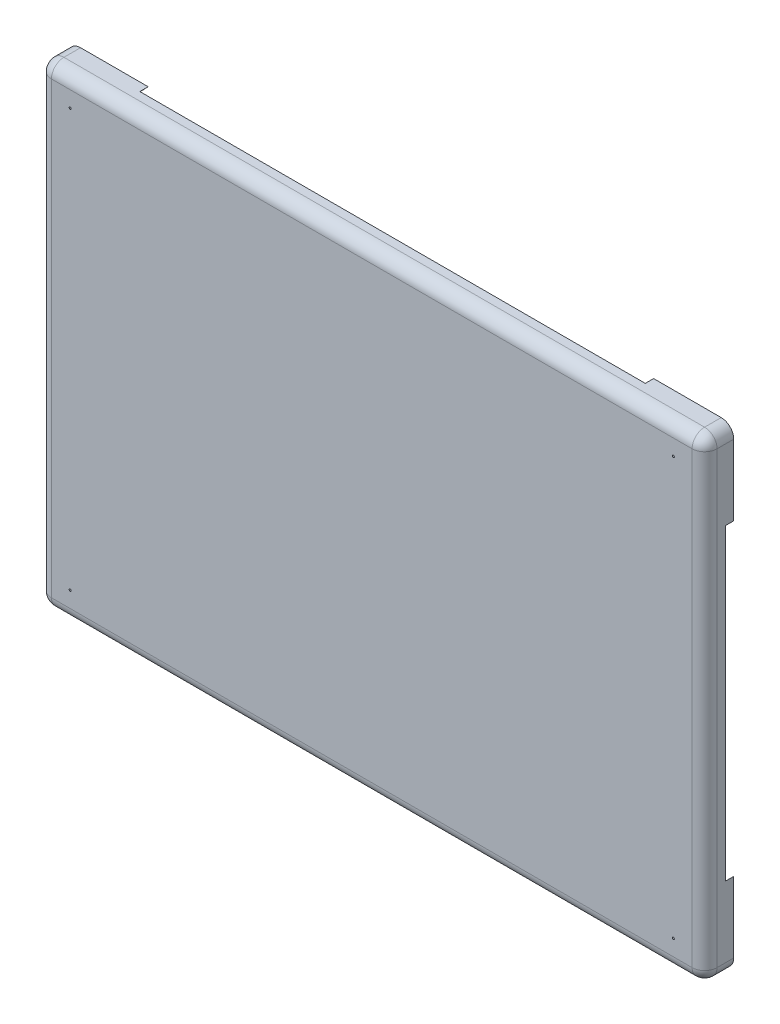
SolidWorks part; units mm, degrees
ref_plane "Front Plane" through (0, 0, 0) normal (0, 0, 1) x (1, 0, 0)
ref_plane "Top Plane" through (0, 0, 0) normal (0, 1, 0) x (1, 0, 0)
ref_plane "Right Plane" through (0, 0, 0) normal (1, 0, 0) x (0, 0, -1)
sketch "Sketch2" plane through (0, 0, 0) normal (0, 0, 1) x (1, 0, 0)
  line L1 (-80, -57) -> (80, -57)
  line L2 (-80, -57) -> (-80, 57)
  line L3 (-80, 57) -> (80, 57)
  line L4 (80, -57) -> (80, 57)
  line L5 (-80, -57) -> (80, 57) construction
  line L6 (-80, 57) -> (80, -57) construction
  point P0 (0, 0)
  dimension "D1" = 160
  dimension "D2" = 114
extrude "Boss-Extrude1" add sketch "Sketch2" along normal blind 5 contours L3 L4 L1 L2
fillet "Fillet1" radius 3 8 edges at (0, 57, 5) (80, 0, 5) (0, -57, 5) (-80, 0, 5) (80, 57, 2.5) (-80, 57, 2.5) (-80, -57, 2.5) (80, -57, 2.5)
sketch "Sketch5" plane through (0, 0, 0) normal (0, 0, -1) x (-1, 0, 0)
  line L0 (-60.75, 57) -> (-80, 37)
  line L1 (77, 57) -> (-77, 57) construction
  line L2 (-80, -54) -> (-80, 54) construction
  line L3 (-80, 37) -> (-80, 54)
  line L4 (-77, 57) -> (-60.75, 57)
  arc A0 (-77, 57) -> (-80, 54) centre (-77, 54) ccw
  point P9 (-80, 57)
  dimension "D4" = 3
  dimension "D1" = 19.25
  dimension "D2" = 20
  dimension "D3" = 27.759
extrude "Boss-Extrude2" add sketch "Sketch5" along normal blind 2
hole_wizard "Ø3.0mm Dowel Hole1" positions "Sketch6" profile "Sketch7" hole size "Ø3.0" standard "ISO"
sketch "Sketch6" plane through (0, 0, -2) normal (0, 0, -1) x (-1, 0, 0)
  line L0 (-80, 54) -> (-80, 37) construction
  line L1 (-60.75, 57) -> (-77, 57) construction
  point P0 (-72.49, 50.17)
  dimension "D1" = 7.51
  dimension "D2" = 6.83
sketch "Sketch7" plane through (72.49, 50.17, -2) normal (1, 0, 0) x (0, 1, 0)
  line L0 (0, 0) -> (0, 7.1515)
  line L1 (0, 7.1515) -> (1.75, 6.1)
  line L2 (1.75, 6.1) -> (1.75, 0)
  line L5 (1.75, 0) -> (0, 0)
  line L10 (0, 7.1515) -> (-1.75, 6.1) construction
  line L11 (0, -6.35) -> (0, 107.95) construction
  dimension "Hole Dia." = 3.5
  dimension "Hole Depth" = 6.1
  dimension "Drill Angle" = 118
mirror "Mirror1" about plane through (0, 0, 0) normal (0, 1, 0) of "Ø3.0mm Dowel Hole1", "Boss-Extrude2" second plane through (0, 0, 0) second plane normal (1, 0, 0)
